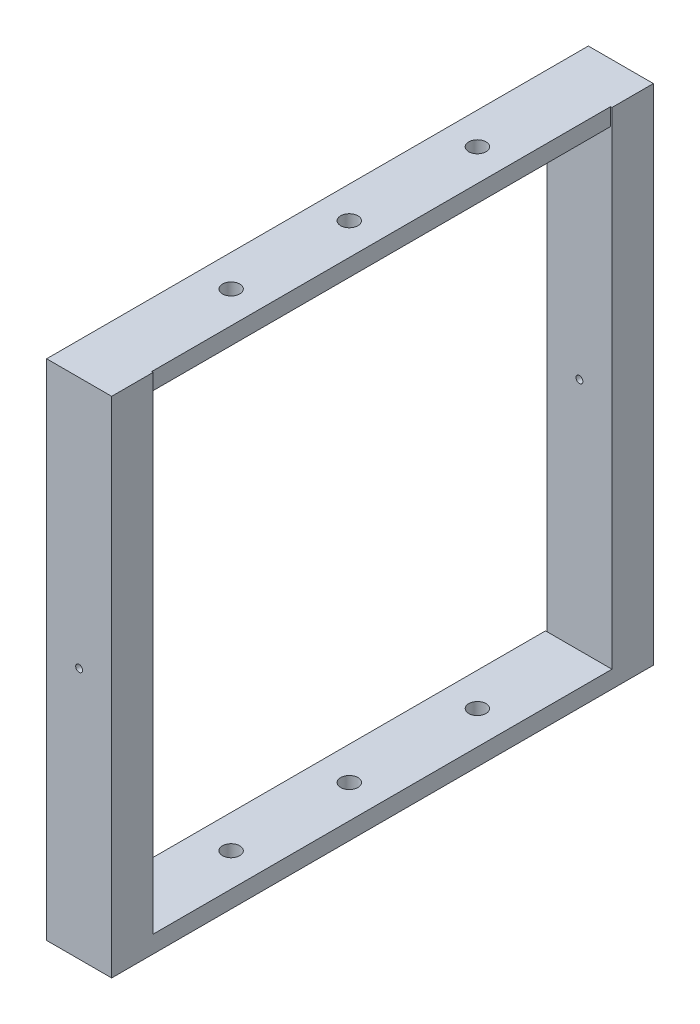
SolidWorks part; units mm, degrees
ref_plane "Front Plane" through (0, 0, 0) normal (0, 0, 1) x (1, 0, 0)
ref_plane "Top Plane" through (0, 0, 0) normal (0, 1, 0) x (1, 0, 0)
ref_plane "Right Plane" through (0, 0, 0) normal (1, 0, 0) x (0, 0, -1)
sketch "Sketch1" plane through (0, 0, 0) normal (0, 1, 0) x (1, 0, 0)
  line L1 (-66.5, -66.5) -> (66.5, -66.5)
  line L2 (-66.5, -66.5) -> (-66.5, 66.5)
  line L3 (-66.5, 66.5) -> (66.5, 66.5)
  line L4 (66.5, -66.5) -> (66.5, 66.5)
  line L5 (-66.5, -66.5) -> (66.5, 66.5) construction
  line L6 (-66.5, 66.5) -> (66.5, -66.5) construction
  point P0 (0, 0)
extrude "Boss-Extrude2" add sketch "Sketch1" along normal blind 136
sketch "Sketch2" plane through (0, 0, 66.5) normal (0, 0, 1) x (1, 0, 0)
  line L0 (66.5, 136) -> (66.5, 0) construction
  line L1 (-66.5, 136) -> (66.5, 136)
  line L2 (-66.5, 136) -> (-66.5, 127)
  line L3 (-66.5, 127) -> (66.5, 127)
  line L4 (66.5, 136) -> (66.5, 127)
  line L6 (-66.5, 0) -> (66.5, 0)
  line L7 (-66.5, 0) -> (-66.5, 9)
  line L8 (-66.5, 9) -> (66.5, 9)
  line L9 (66.5, 0) -> (66.5, 9)
  line L10 (-66.5, 127) -> (66.5, 127)
  line L11 (-66.5, 127) -> (-66.5, 9)
  line L12 (-66.5, 9) -> (66.5, 9)
  line L13 (66.5, 127) -> (66.5, 9)
  line M2 (66.5, 0) -> (66.5, 136)
  line M4 (-66.5, 136) -> (-66.5, 0)
extrude "Cut-Extrude1" cut sketch "Sketch2" against normal blind 136 contours L8 L3 M4 M2
sketch "Sketch4" plane through (0, 9, 0) normal (0, 1, 0) x (1, 0, 0)
  line L0 (0, 66.5) -> (0, -66.5) construction
  line L1 (-66.5, 66.5) -> (66.5, 66.5) construction
  line L2 (-66.5, -66.5) -> (66.5, -66.5) construction
  line L3 (0, -66.5) -> (33.25, -66.5) construction
  line L4 (33.25, -66.5) -> (33.25, 66.5) construction
  line L5 (0, 0) -> (66.5, 0) construction
  line L6 (66.5, 66.5) -> (66.5, -66.5) construction
  line L7 (66.5, 0) -> (66.5, 33.25) construction
  line L8 (66.5, 33.25) -> (0, 33.25) construction
  line L9 (0, 33.25) -> (0, -33.25) construction
  line L10 (0, -33.25) -> (66.5, -33.25) construction
  line L11 (43.75, 43.75) -> (22.75, 43.75)
  line L12 (43.75, -22.75) -> (22.75, -22.75)
  line L13 (43.75, -22.75) -> (43.75, -43.75)
  line L14 (43.75, -43.75) -> (22.75, -43.75)
  line L15 (22.75, -22.75) -> (22.75, -43.75)
  line L16 (43.75, -22.75) -> (22.75, -43.75) construction
  line L17 (43.75, -43.75) -> (22.75, -22.75) construction
  line L18 (46.25, -20.25) -> (20.25, -20.25)
  line L19 (46.25, -20.25) -> (46.25, -46.25)
  line L20 (46.25, -46.25) -> (20.25, -46.25)
  line L21 (20.25, -20.25) -> (20.25, -46.25)
  line L22 (46.25, -20.25) -> (20.25, -46.25) construction
  line L23 (46.25, -46.25) -> (20.25, -20.25) construction
  line L24 (22.75, 22.75) -> (22.75, 43.75)
  line L25 (43.75, 22.75) -> (22.75, 22.75)
  line L26 (43.75, 22.75) -> (43.75, 43.75)
  line L27 (46.25, 46.25) -> (20.25, 46.25)
  line L28 (20.25, 20.25) -> (20.25, 46.25)
  line L29 (46.25, 20.25) -> (20.25, 20.25)
  line L30 (46.25, 20.25) -> (46.25, 46.25)
  line L31 (46.25, 46.25) -> (20.25, 20.25) construction
  line L32 (46.25, 20.25) -> (20.25, 46.25) construction
  line L34 (43.75, -43.75) -> (46.25, -43.75)
  line L35 (43.75, -43.75) -> (43.75, -22.75)
  line L36 (43.75, -22.75) -> (46.25, -22.75)
  line L37 (46.25, -43.75) -> (46.25, -22.75)
  line L38 (43.75, 22.75) -> (46.25, 22.75)
  line L39 (43.75, 22.75) -> (43.75, 43.75)
  line L40 (43.75, 43.75) -> (46.25, 43.75)
  line L41 (46.25, 22.75) -> (46.25, 43.75)
  point P18 (33.25, -33.25)
  point P23 (33.25, -33.25)
  point P36 (33.25, 33.25)
extrude "Boss-Extrude3" add sketch "Sketch4" along normal blind 10.5 contours L12 L36 L19 L18 L21 L20 L34 L14 L15 | L11 L40 L30 L27 L28 L29 L38 L25 L24
sketch "Sketch5" plane through (22.75, 0, 0) normal (1, 0, 0) x (0, 0, -1)
  line L0 (-22.75, 19.5) -> (-22.75, 9) construction
  line L1 (-43.75, 19.5) -> (-22.75, 19.5)
  line L2 (-43.75, 19.5) -> (-43.75, 16.5)
  line L3 (-43.75, 16.5) -> (-22.75, 16.5)
  line L4 (-22.75, 19.5) -> (-22.75, 16.5)
  line L5 (43.75, 19.5) -> (43.75, 9) construction
  line L6 (22.75, 19.5) -> (43.75, 19.5)
  line L7 (22.75, 19.5) -> (22.75, 16.5)
  line L8 (22.75, 16.5) -> (43.75, 16.5)
  line L9 (43.75, 19.5) -> (43.75, 16.5)
extrude "Boss-Extrude4" add sketch "Sketch5" along normal up to surface (23.5 mm away) up to face at (46.25, 14.25, 45)
sketch "Sketch6" plane through (0, 19.5, 0) normal (0, 1, 0) x (1, 0, 0)
  line L0 (46.25, -46.25) -> (46.25, -20.25) construction
  line L1 (46.25, 20.25) -> (46.25, 46.25) construction
  line L2 (67.25, -41.85) -> (25.25, -41.85)
  line L3 (67.25, -41.85) -> (67.25, -24.65)
  line L4 (67.25, -24.65) -> (25.25, -24.65)
  line L5 (25.25, -41.85) -> (25.25, -24.65)
  line L6 (67.25, -41.85) -> (25.25, -24.65) construction
  line L7 (67.25, -24.65) -> (25.25, -41.85) construction
  line L9 (67.25, 24.65) -> (25.25, 24.65)
  line L10 (67.25, 24.65) -> (67.25, 41.85)
  line L11 (67.25, 41.85) -> (25.25, 41.85)
  line L12 (25.25, 24.65) -> (25.25, 41.85)
  line L13 (67.25, 24.65) -> (25.25, 41.85) construction
  line L14 (67.25, 41.85) -> (25.25, 24.65) construction
  point P4 (46.25, -33.25)
  point P13 (46.25, 33.25)
extrude "Cut-Extrude2" cut sketch "Sketch6" against normal up to surface (3 mm away) up to face at (34.5, 16.5, -33.25)
sketch "Sketch7" plane through (0, 127, 0) normal (0, -1, 0) x (1, 0, 0)
  line L0 (0, 66.5) -> (0, -66.5) construction
  line L1 (-66.5, 66.5) -> (66.5, 66.5) construction
  line L2 (-66.5, -66.5) -> (66.5, -66.5) construction
  line L3 (0, -66.5) -> (-33.25, -66.5) construction
  line L4 (-33.25, -66.5) -> (-33.25, 66.5) construction
  line L5 (-33.25, 66.5) -> (-66.5, 66.5) construction
  line L6 (-66.5, 66.5) -> (-66.5, 0) construction
  line L8 (-66.5, 0) -> (0, 0) construction
  line L9 (0, 0) -> (0, -33.25) construction
  line L10 (0, -33.25) -> (-66.5, -33.25) construction
  line L11 (-66.5, -66.5) -> (-66.5, 66.5) construction
  line L12 (-66.5, -33.25) -> (-66.5, 33.25) construction
  line L13 (-66.5, 33.25) -> (0, 33.25) construction
  line L14 (-22.75, -22.75) -> (-43.75, -22.75)
  line L15 (-22.75, 43.75) -> (-43.75, 43.75)
  line L16 (-22.75, 43.75) -> (-22.75, 22.75)
  line L17 (-22.75, 22.75) -> (-43.75, 22.75)
  line L18 (-43.75, 43.75) -> (-43.75, 22.75)
  line L19 (-22.75, 43.75) -> (-43.75, 22.75) construction
  line L20 (-22.75, 22.75) -> (-43.75, 43.75) construction
  line L21 (-20.25, 46.25) -> (-46.25, 46.25)
  line L22 (-20.25, 46.25) -> (-20.25, 20.25)
  line L23 (-20.25, 20.25) -> (-46.25, 20.25)
  line L24 (-46.25, 46.25) -> (-46.25, 20.25)
  line L25 (-20.25, 46.25) -> (-46.25, 20.25) construction
  line L26 (-20.25, 20.25) -> (-46.25, 46.25) construction
  line L27 (-43.75, -43.75) -> (-43.75, -22.75)
  line L28 (-22.75, -43.75) -> (-43.75, -43.75)
  line L29 (-22.75, -43.75) -> (-22.75, -22.75)
  line L30 (-20.25, -20.25) -> (-46.25, -20.25)
  line L31 (-46.25, -46.25) -> (-46.25, -20.25)
  line L32 (-20.25, -46.25) -> (-46.25, -46.25)
  line L33 (-20.25, -46.25) -> (-20.25, -20.25)
  line L34 (-20.25, -20.25) -> (-46.25, -46.25) construction
  line L35 (-20.25, -46.25) -> (-46.25, -20.25) construction
  line L36 (-43.75, -22.75) -> (-46.25, -22.75)
  line L37 (-43.75, 43.75) -> (-46.25, 43.75)
  line L38 (-43.75, 43.75) -> (-43.75, 22.75)
  line L39 (-43.75, 22.75) -> (-46.25, 22.75)
  line L40 (-46.25, 43.75) -> (-46.25, 22.75)
  line L41 (-46.25, -43.75) -> (-46.25, -22.75)
  line L42 (-43.75, -43.75) -> (-46.25, -43.75)
  line L43 (-43.75, -43.75) -> (-43.75, -22.75)
  point P17 (-33.25, 33.25)
  point P24 (-33.25, 33.25)
  point P37 (-33.25, -33.25)
extrude "Boss-Extrude5" add sketch "Sketch7" along normal blind 10.5 contours L17 L39 L24 L23 L22 L21 L37 L15 L16 | L28 L42 L31 L32 L33 L30 L36 L14 L29
sketch "Sketch8" plane through (-22.75, 0, 0) normal (-1, 0, 0) x (0, 0, 1)
  line L0 (22.75, 116.5) -> (22.75, 127) construction
  line L1 (43.75, 116.5) -> (22.75, 116.5)
  line L2 (43.75, 116.5) -> (43.75, 119.5)
  line L3 (43.75, 119.5) -> (22.75, 119.5)
  line L4 (22.75, 116.5) -> (22.75, 119.5)
  line L5 (-22.75, 116.5) -> (-22.75, 127) construction
  line L6 (-43.75, 116.5) -> (-22.75, 116.5)
  line L7 (-43.75, 116.5) -> (-43.75, 119.5)
  line L8 (-43.75, 119.5) -> (-22.75, 119.5)
  line L9 (-22.75, 116.5) -> (-22.75, 119.5)
extrude "Boss-Extrude6" add sketch "Sketch8" along normal up to surface (23.5 mm away) up to face at (-46.25, 121.75, 45)
sketch "Sketch9" plane through (0, 116.5, 0) normal (0, -1, 0) x (1, 0, 0)
  line L0 (-46.25, 46.25) -> (-46.25, 20.25) construction
  line L1 (-46.25, 20.25) -> (-46.25, -20.25) construction
  line L2 (-46.25, -20.25) -> (-46.25, -46.25) construction
  line L4 (-67.25, 41.85) -> (-25.25, 41.85)
  line L5 (-67.25, 41.85) -> (-67.25, 24.65)
  line L6 (-67.25, 24.65) -> (-25.25, 24.65)
  line L7 (-25.25, 41.85) -> (-25.25, 24.65)
  line L8 (-67.25, 41.85) -> (-25.25, 24.65) construction
  line L9 (-67.25, 24.65) -> (-25.25, 41.85) construction
  line L10 (-67.25, -24.65) -> (-25.25, -24.65)
  line L11 (-67.25, -24.65) -> (-67.25, -41.85)
  line L12 (-67.25, -41.85) -> (-25.25, -41.85)
  line L13 (-25.25, -24.65) -> (-25.25, -41.85)
  line L14 (-67.25, -24.65) -> (-25.25, -41.85) construction
  line L15 (-67.25, -41.85) -> (-25.25, -24.65) construction
  point P4 (-46.25, 33.25)
  point P13 (-46.25, -33.25)
extrude "Cut-Extrude3" cut sketch "Sketch9" against normal up to surface (3 mm away) up to face at (-34.5, 119.5, 33.25)
sketch "Sketch10" plane through (0, 0, 0) normal (0, -1, 0) x (1, 0, 0)
  line L0 (-66.5, -66.5) -> (66.5, -66.5) construction
  line L1 (66.5, -66.5) -> (0, -66.5) construction
  line L2 (0, -66.5) -> (0, 66.5) construction
  line L3 (-66.5, 66.5) -> (66.5, 66.5) construction
  line L5 (-9.6307, -66.5) -> (9.6307, -66.5)
  line L6 (-9.6307, -66.5) -> (-9.6307, 66.5)
  line L7 (-9.6307, 66.5) -> (9.6307, 66.5)
  line L8 (9.6307, -66.5) -> (9.6307, 66.5)
  line L9 (-9.6307, -66.5) -> (9.6307, 66.5) construction
  line L10 (-9.6307, 66.5) -> (9.6307, -66.5) construction
  point P4 (0, 0)
extrude "Boss-Extrude7" add sketch "Sketch10" along normal blind 5
sketch "Sketch11" plane through (0, 136, 0) normal (0, 1, 0) x (1, 0, 0)
  line L0 (-66.5, -66.5) -> (66.5, -66.5) construction
  line L1 (66.5, -66.5) -> (0, -66.5) construction
  line L2 (0, -66.5) -> (0, 66.5) construction
  line L3 (66.5, 66.5) -> (-66.5, 66.5) construction
  line L4 (0, 66.5) -> (0, 0) construction
  line L6 (-9.2186, -66.5) -> (9.2186, -66.5)
  line L7 (-9.2186, -66.5) -> (-9.2186, 66.5)
  line L8 (-9.2186, 66.5) -> (9.2186, 66.5)
  line L9 (9.2186, -66.5) -> (9.2186, 66.5)
  line L10 (-9.2186, -66.5) -> (9.2186, 66.5) construction
  line L11 (-9.2186, 66.5) -> (9.2186, -66.5) construction
extrude "Boss-Extrude8" add sketch "Sketch11" along normal blind 5
sketch "Sketch12" plane through (0, 0, -66.5) normal (0, 0, -1) x (-1, 0, 0)
  line L1 (-9.6307, -5) -> (9.2186, -5)
  line L2 (-9.6307, -5) -> (-9.6307, 141)
  line L3 (-9.6307, 141) -> (9.2186, 141)
  line L4 (9.2186, -5) -> (9.2186, 141)
extrude "Boss-Extrude9" add sketch "Sketch12" along normal blind 12
sketch "Sketch14" plane through (0, 0, 66.5) normal (0, 0, 1) x (1, 0, 0)
  line L1 (-9.2186, 141) -> (9.6307, 141)
  line L2 (-9.2186, 141) -> (-9.2186, -5)
  line L3 (-9.2186, -5) -> (9.6307, -5)
  line L4 (9.6307, 141) -> (9.6307, -5)
extrude "Boss-Extrude10" add sketch "Sketch14" along normal blind 12
sketch "Sketch17" plane through (0, 0, 78.5) normal (0, 0, 1) x (1, 0, 0)
  line L0 (-9.2186, 141) -> (9.6307, -5) construction
  line L1 (9.6307, -5) -> (0.2061, 68) construction
  circle A0 centre (0.2061, 68) radius 1
extrude "Cut-Extrude4" cut sketch "Sketch17" against normal through all
sketch "Sketch18" plane through (-66.5, 0, 0) normal (-1, 0, 0) x (0, 0, 1)
  line L0 (66.5, 9) -> (66.5, -5) construction
  line L1 (-66.5, 136) -> (66.5, 136)
  line L2 (-66.5, 136) -> (-66.5, 0)
  line L3 (-66.5, 0) -> (66.5, 0)
  line L4 (66.5, 136) -> (66.5, 0)
  line L5 (66.5, -5) -> (66.5, 0) construction
extrude "Cut-Extrude5" cut sketch "Sketch18" against normal blind 170
sketch "Sketch20" plane through (0, 0, 0) normal (0, 1, 0) x (1, 0, 0)
  circle A0 centre (0, 0) radius 2.5
extrude "Cut-Extrude6" cut sketch "Sketch20" against normal blind 10
sketch "Sketch21" plane through (0, -5, 0) normal (0, -1, 0) x (-1, 0, 0)
  circle A0 centre (2.8846, 0.7634) radius 0.25
sketch "Sketch22" plane through (0, 0, 0) normal (0, 1, 0) x (1, 0, 0)
  circle A0 centre (0, 0) radius 2.5
extrude "Cut-Extrude8" cut sketch "Sketch22" along normal blind 170
sketch "Sketch24" plane through (0, 0, 0) normal (0, 1, 0) x (1, 0, 0)
  circle A0 centre (0, 59.1598) radius 2.5
extrude "Cut-Extrude9" cut sketch "Sketch24" against normal blind 170
sketch "Sketch26" plane through (0, 9, 0) normal (0, 1, 0) x (1, 0, 0)
  circle A0 centre (0, 59.1598) radius 2.4747
extrude "Cut-Extrude10" cut sketch "Sketch26" along normal blind 177
sketch "Sketch27" plane through (0, 0, 0) normal (0, 1, 0) x (1, 0, 0)
  circle A0 centre (0, -59.4995) radius 2.5
extrude "Cut-Extrude11" cut sketch "Sketch27" against normal blind 177
sketch "Sketch29" plane through (0, -5, 0) normal (0, -1, 0) x (1, 0, 0)
  circle A0 centre (0, 59.4995) radius 2.5
extrude "Cut-Extrude12" cut sketch "Sketch29" against normal blind 177
sketch "Sketch30" plane through (0, 141, 0) normal (0, 1, 0) x (1, 0, 0)
  circle A0 centre (0, 37.1264) radius 2.5
extrude "Cut-Extrude13" cut sketch "Sketch30" against normal blind 178
sketch "Sketch31" plane through (0, 141, 0) normal (0, 1, 0) x (1, 0, 0)
  circle A0 centre (0, -34.2453) radius 2.5
extrude "Cut-Extrude14" cut sketch "Sketch31" against normal blind 178
sketch "Sketch32" plane through (0, 141, 0) normal (0, 1, 0) x (1, 0, 0)
  circle A0 centre (0, 59.1598) radius 2.4747
  circle A1 centre (0, -59.4995) radius 2.5
extrude "Boss-Extrude11" add sketch "Sketch32" against normal blind 5
sketch "Sketch33" plane through (0, -5, 0) normal (0, -1, 0) x (1, 0, 0)
  circle A0 centre (0, -59.1598) radius 2.5
  circle A1 centre (0, 59.4995) radius 2.5
extrude "Boss-Extrude12" add sketch "Sketch33" against normal blind 5
